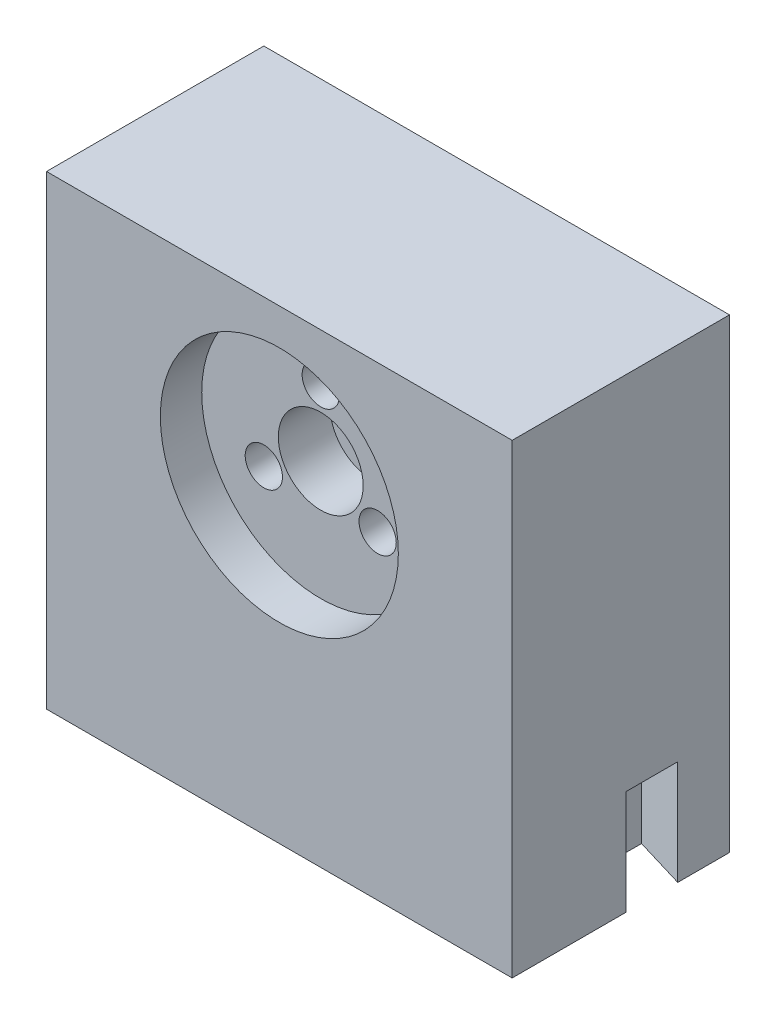
SolidWorks part; units mm, degrees
ref_plane "Front Plane" through (0, 0, 0) normal (0, 0, 1) x (1, 0, 0)
ref_plane "Top Plane" through (0, 0, 0) normal (0, 1, 0) x (1, 0, 0)
ref_plane "Right Plane" through (0, 0, 0) normal (1, 0, 0) x (0, 0, -1)
sketch "Sketch1" plane through (0, 0, 0) normal (0, 0, 1) x (1, 0, 0)
  line L1 (0, 0) -> (45, 0)
  line L2 (0, 0) -> (0, 45)
  line L3 (0, 45) -> (45, 45)
  line L4 (45, 0) -> (45, 45)
  dimension "D1" = 45
  dimension "D2" = 45
extrude "Boss-Extrude1" add sketch "Sketch1" along normal blind 15
sketch "Sketch2" plane through (0, 0, 15) normal (0, 0, 1) x (1, 0, 0)
  line L0 (0, 0) -> (45, 0) construction
  line L1 (22.5, 45) -> (22.5, 0) construction
  line L2 (45, 45) -> (0, 45) construction
  line L3 (14.5, 0) -> (30.5, 0)
  line L4 (14.5, 0) -> (14.5, 2)
  line L5 (14.5, 2) -> (21.5, 2)
  line L6 (30.5, 0) -> (30.5, 2)
  line L7 (23.5, 2) -> (30.5, 2)
  line L9 (21.5, 2) -> (21.5, 10)
  line L10 (21.5, 10) -> (23.5, 10)
  line L11 (23.5, 2) -> (23.5, 10)
  point P14 (22.5, 0)
  dimension "D1" = 16
  dimension "D2" = 2
  dimension "D3" = 2
  dimension "D5" = 8
extrude "Cut-Extrude1" cut sketch "Sketch2" against normal through all
sketch "Sketch3" plane through (0, 0, 0) normal (0, -1, 0) x (1, 0, 0)
  line L0 (45, 10) -> (40, 11.5)
  line L1 (45, 15) -> (45, 0) construction
  line L2 (40, 11.5) -> (40, 3.5)
  line L3 (40, 3.5) -> (45, 5)
  line L4 (45, 10) -> (45, 5)
  point P7 (45, 7.5)
  dimension "D1" = 8
  dimension "D2" = 5
  dimension "D3" = 5
extrude "Cut-Extrude2" cut sketch "Sketch3" against normal blind 10.1
ref_plane "Plane1" through (22.5, 0, 0) normal (1, 0, 0) x (0, 0, -1)
mirror "Mirror1" about plane through (22.5, 0, 0) normal (1, 0, 0) of "Cut-Extrude2"
sketch "Sketch4" plane through (0, 0, 15) normal (0, 0, 1) x (1, 0, 0)
  line L1 (0, 45) -> (45, 45)
  line L2 (0, 45) -> (0, 0)
  line L3 (0, 0) -> (45, 0)
  line L4 (45, 45) -> (45, 0)
extrude "Boss-Extrude2" add sketch "Sketch4" along normal blind 3
sketch "Sketch5" plane through (0, 0, 18) normal (0, 0, 1) x (1, 0, 0)
  line L0 (0, 0) -> (45, 0) construction
  circle A0 centre (22.5, 0) radius 17.5
  dimension "D1" = 35
extrude "Cut-Extrude3" cut sketch "Sketch5" against normal up to surface (3 mm away) up to face at (21.5, 3.5, 15)
sketch "Sketch6" plane through (0, 0, 18) normal (0, 0, 1) x (1, 0, 0)
  line L1 (0, 45) -> (45, 45)
  line L2 (0, 45) -> (0, 0)
  line L3 (0, 0) -> (45, 0)
  line L4 (45, 45) -> (45, 0)
extrude "Boss-Extrude3" add sketch "Sketch6" along normal blind 3
sketch "Sketch7" plane through (0, 0, 21) normal (0, 0, 1) x (1, 0, 0)
  line L0 (0, 30) -> (45, 30) construction
  line L1 (0, 45) -> (0, 0) construction
  line L2 (45, 0) -> (45, 45) construction
  line L3 (45, 45) -> (0, 45) construction
  circle A0 centre (22.5, 30) radius 2.6
  dimension "D2" = 5.2
  dimension "D1" = 15
extrude "Cut-Extrude4" cut sketch "Sketch7" against normal through all
sketch "Sketch8" plane through (0, 0, 21) normal (0, 0, 1) x (1, 0, 0)
  circle A0 centre (22.5, 30) radius 6.35 construction
  circle A1 centre (22.5, 36.35) radius 1.8
  circle A2 centre (27.9993, 26.825) radius 1.8
  circle A3 centre (17.0007, 26.825) radius 1.8
  point P11 (22.5, 30)
  dimension "D1" = 12.7
  dimension "D2" = 3.6
  dimension "D3" = 3
extrude "Cut-Extrude5" cut sketch "Sketch8" against normal through all
sketch "Sketch9" plane through (0, 0, 21) normal (0, 0, 1) x (1, 0, 0)
  circle A0 centre (22.5, 30) radius 11.5
  dimension "D1" = 23
extrude "Cut-Extrude6" cut sketch "Sketch9" against normal blind 4
sketch "Sketch10" plane through (0, 0, 17) normal (0, 0, 1) x (1, 0, 0)
  circle A0 centre (22.5, 30) radius 4.1
  dimension "D1" = 8.2
extrude "Cut-Extrude7" cut sketch "Sketch10" against normal blind 5
